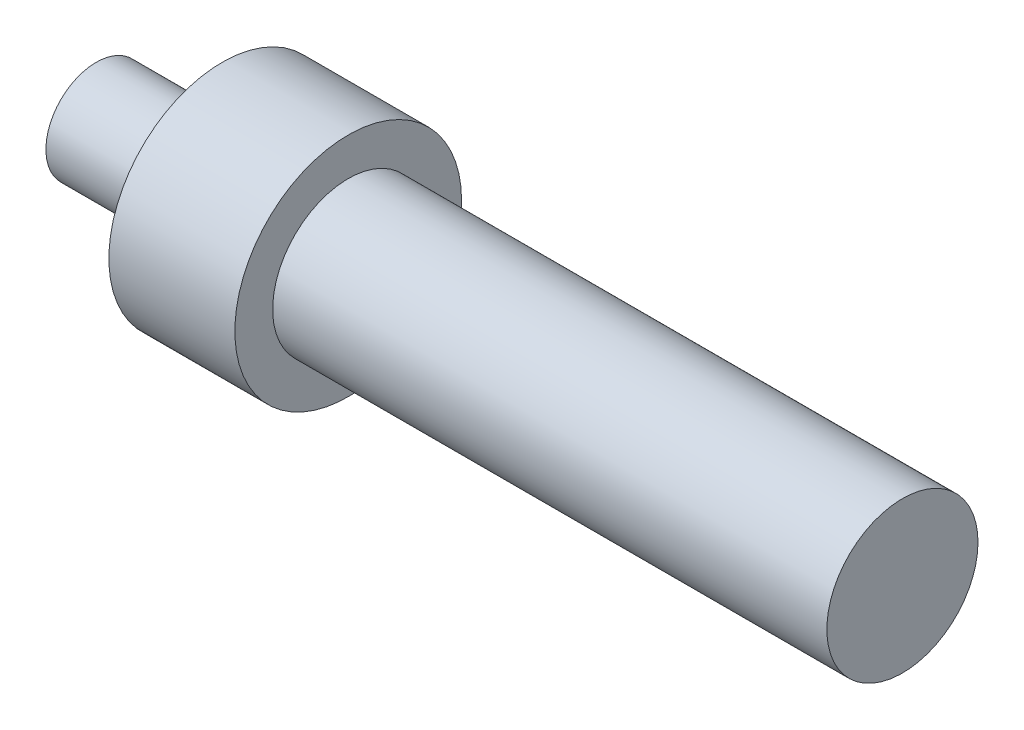
SolidWorks part; units mm, degrees
ref_plane "Plano frontal" through (0, 0, 0) normal (0, 0, 1) x (1, 0, 0)
ref_plane "Plano superior" through (0, 0, 0) normal (0, 1, 0) x (1, 0, 0)
ref_plane "Plano direito" through (0, 0, 0) normal (1, 0, 0) x (0, 0, -1)
sketch "Sketch1" plane through (0, 0, 0) normal (0, 0, 1) x (1, 0, 0)
  line L0 (0, 0) -> (0, 4)
  line L1 (0, 4) -> (10, 4)
  line L2 (10, 4) -> (10, 9)
  line L3 (10, 9) -> (20, 9)
  line L4 (20, 9) -> (20, 6)
  line L5 (20, 6) -> (64, 6)
  line L6 (64, 6) -> (64, 0)
  line L7 (64, 0) -> (0, 0)
  line L8 (0, 0) -> (-6.0275, 0) construction
  dimension "D1" = 8
  dimension "D2" = 10
  dimension "D3" = 10
  dimension "D4" = 18
  dimension "D5" = 12
  dimension "D6" = 44
revolve "Revolve1" add sketch "Sketch1" angle 360 about L8
ref_point "Point1"
ref_point "Point2"
